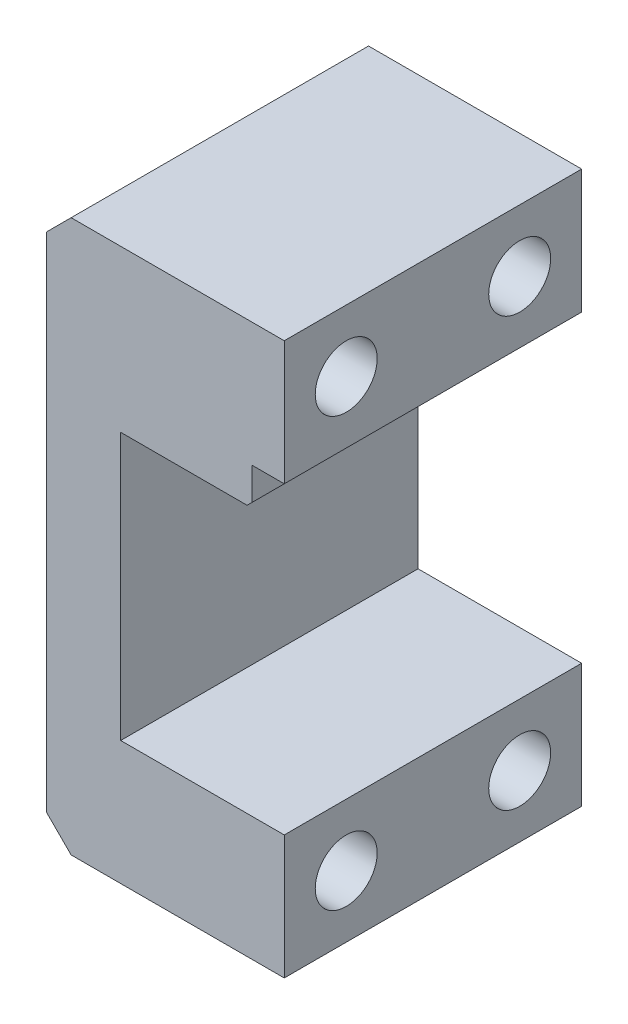
SolidWorks part; units mm, degrees
material "AISI 304"
ref_plane "前视基准面" through (0, 0, 0) normal (0, 0, 1) x (1, 0, 0)
ref_plane "上视基准面" through (0, 0, 0) normal (0, 1, 0) x (1, 0, 0)
ref_plane "右视基准面" through (0, 0, 0) normal (1, 0, 0) x (0, 0, -1)
sketch "草图1" plane through (0, 0, 0) normal (0, 0, 1) x (1, 0, 0)
  line L0 (0, 0) -> (0, 22.27)
  line L1 (0, 22.27) -> (9.6, 22.27)
  line L2 (9.6, 22.27) -> (9.6, 17.27)
  line L3 (9.6, 17.27) -> (8.3, 17.27)
  line L4 (8.3, 17.27) -> (8.3, 15.77)
  line L5 (8.3, 15.77) -> (3, 15.77)
  line L6 (3, 15.77) -> (3, 5)
  line L7 (3, 5) -> (9.6, 5)
  line L8 (9.6, 5) -> (9.6, 0)
  line L9 (9.6, 0) -> (0, 0)
  line L10 (9.6, 5) -> (9.6, 17.27) construction
  dimension "D1" = 5
  dimension "D2" = 10.77
  dimension "D3" = 3
  dimension "D4" = 1.3
  dimension "D5" = 6.6
  dimension "D6" = 1.5
  dimension "D7" = 5
extrude "凸台-拉伸1" add sketch "草图1" along normal blind 12
chamfer "倒角1" distance 0.2 angle 45 1 edges at (8.3, 15.77, 6)
sketch "草图2" plane through (0, 0, 0) normal (-1, 0, 0) x (0, 0, 1)
  line L0 (6, 22.27) -> (6, 0) construction
  line L1 (12, 22.27) -> (0, 22.27) construction
  line L2 (12, 0) -> (0, 0) construction
  line L3 (2.5, 19.77) -> (9.5, 19.77) construction
  line L4 (2.5, 2.5) -> (9.5, 2.5) construction
  line L5 (9.5, 2.5) -> (9.5, 19.77) construction
  line L6 (12, 22.27) -> (12, 0) construction
  circle A0 centre (9.5, 19.77) radius 1.5
  circle A1 centre (2.5, 19.77) radius 1.5
  circle A2 centre (2.5, 2.5) radius 1.5
  circle A3 centre (9.5, 2.5) radius 1.5
  point P9 (6, 19.77)
  point P12 (6, 2.5)
  dimension "D3" = 3
  dimension "D1" = 2.5
  dimension "D2" = 2.5
  dimension "D4" = 2.5
hole_wizard "M3 螺纹孔2" positions "3D草图3" profile "草图5" tap size "M3" standard "GB" end condition through all
sketch3d "3D草图3"
  point P0 (0, 2.5, 2.5)
  point P3 (0, 2.5, 9.5)
  point P6 (0, 19.77, 9.5)
  point P9 (0, 19.77, 2.5)
sketch "草图5" plane through (0, 2.5, 2.5) normal (0, 1, 0) x (0, 0, 1)
  line L0 (0, 0) -> (0, 9.6)
  line L1 (0, 9.6) -> (1.25, 9.6)
  line L2 (1.25, 9.6) -> (1.25, 0)
  line L5 (1.25, 0) -> (0, 0)
  line L11 (0, -6.35) -> (0, 107.95) construction
  dimension "通孔螺纹孔钻头直径" = 2.5
  dimension "通孔螺纹孔钻头深度" = 9.6
cosmetic thread "孔螺蚊线5"
cosmetic thread "孔螺蚊线6"
cosmetic thread "孔螺蚊线7"
cosmetic thread "孔螺蚊线8"
chamfer "倒角2" distance 1 angle 45 2 edges at (0, 0, 6) (0, 22.27, 6)
